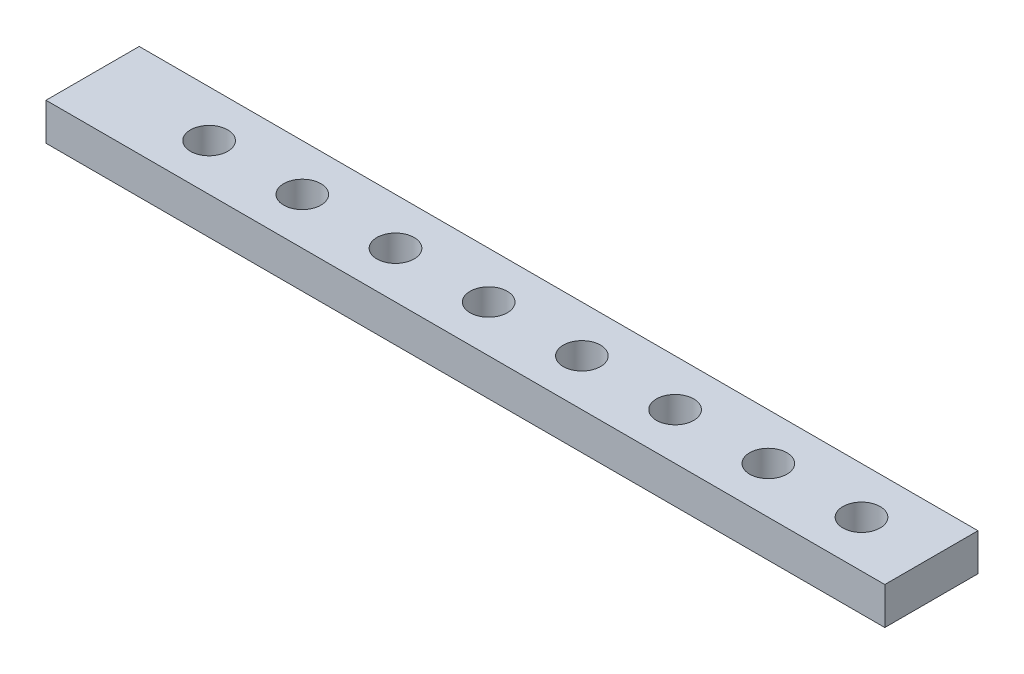
SolidWorks part; units mm, degrees
ref_plane "Front Plane" through (0, 0, 0) normal (0, 0, 1) x (1, 0, 0)
ref_plane "Top Plane" through (0, 0, 0) normal (0, 1, 0) x (1, 0, 0)
ref_plane "Right Plane" through (0, 0, 0) normal (1, 0, 0) x (0, 0, -1)
sketch "Sketch1" plane through (0, 0, 0) normal (0, 1, 0) x (1, 0, 0)
  line L1 (0, 0) -> (210, 0)
  line L2 (0, 0) -> (0, 20)
  line L3 (0, 20) -> (210, 20)
  line L4 (210, 0) -> (210, 20)
  dimension "D1" = 210
  dimension "D2" = 20
extrude "Boss-Extrude1" add sketch "Sketch1" along normal blind 8
sketch "Sketch2" plane through (0, 8, 0) normal (0, 1, 0) x (1, 0, 0)
  line L0 (210, 20) -> (0, 20) construction
  line L1 (210, 0) -> (210, 20) construction
  circle A0 centre (195, 10) radius 4
  dimension "D1" = 8
  dimension "D3" = 15
  dimension "D2" = 10
extrude "Cut-Extrude1" cut sketch "Sketch2" against normal blind 10
pattern_linear "LPattern1" count 8 spacing 20 along (-1, 0, 0) of "Cut-Extrude1"
sketch "Sketch4" plane through (0, 0, 0) normal (0, 1, 0) x (1, 0, 0)
  line L0 (-50, 20) -> (-50, 0) construction
  line L1 (210, 20) -> (-50, 20) construction
  line L2 (210, 20) -> (210, 0) construction
  line L3 (210, 0) -> (-50, 0) construction
  line L5 (0, 0) -> (210, 0) construction
  line L7 (-50, 20) -> (30, 20)
  line L8 (-50, 20) -> (-50, 0)
  line L9 (-50, 0) -> (30, 0)
  line L10 (30, 20) -> (30, 0)
  arc A0 (-50, 20) -> (-50, 0) centre (-50, 10) ccw construction
  dimension "D1" = 260
  dimension "D2" = 80
extrude "Cut-Extrude2" cut sketch "Sketch4" along normal blind 10
